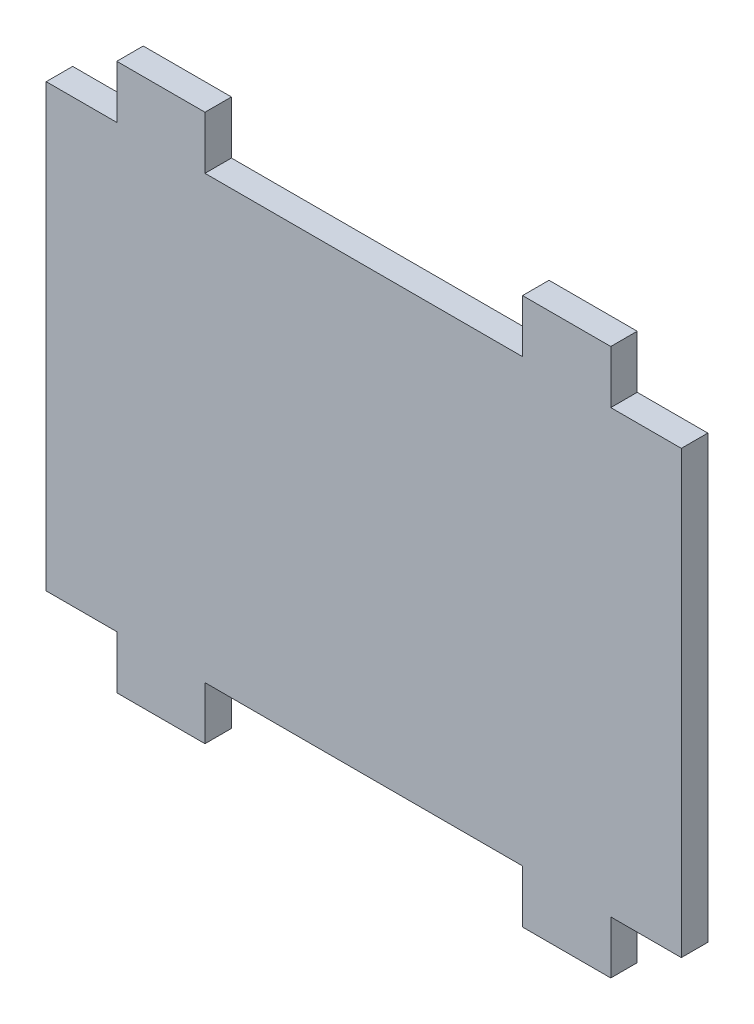
SolidWorks part; units mm, degrees
ref_plane "Plan de face" through (0, 0, 0) normal (0, 0, 1) x (1, 0, 0)
ref_plane "Plan de dessus" through (0, 0, 0) normal (0, 1, 0) x (1, 0, 0)
ref_plane "Plan de droite" through (0, 0, 0) normal (1, 0, 0) x (0, 0, -1)
sketch "Esquisse1" plane through (0, 0, 0) normal (0, 0, 1) x (1, 0, 0)
  line L1 (0, 0) -> (-72, 0)
  line L2 (0, 0) -> (0, 50)
  line L3 (-72, 50) -> (0, 50)
  line L4 (-72, 0) -> (-72, 50)
  dimension "D1" = 50
  dimension "D2" = 72
extrude "Boss.-Extru.1" add sketch "Esquisse1" along normal blind 3
sketch "Esquisse2" plane through (0, 0, 3) normal (0, 0, 1) x (1, 0, 0)
  line L1 (-72, 0) -> (0, 0) construction
  line L2 (-64, 0) -> (-54, 0)
  line L3 (-64, 0) -> (-64, -6)
  line L4 (-64, -6) -> (-54, -6)
  line L5 (-54, 0) -> (-54, -6)
  line L7 (-36, 50) -> (-36, 0) construction
  line L8 (0, 50) -> (-72, 50) construction
  line L10 (-54, 50) -> (-54, 56)
  line L11 (-64, 56) -> (-54, 56)
  line L12 (-64, 50) -> (-64, 56)
  line L13 (-64, 50) -> (-54, 50)
  line L14 (-128, 25) -> (0, 25) construction
  line L15 (-8, 50) -> (-18, 50)
  line L16 (-8, 50) -> (-8, 56)
  line L17 (-8, 56) -> (-18, 56)
  line L18 (-18, 50) -> (-18, 56)
  line L19 (-18, 0) -> (-18, -6)
  line L20 (-8, -6) -> (-18, -6)
  line L21 (-8, 0) -> (-8, -6)
  line L22 (-8, 0) -> (-18, 0)
  dimension "D1" = 18
  dimension "D2" = 6
  dimension "D3" = 0
  dimension "D4" = 10
  dimension "D5" = 25
extrude "Boss.-Extru.2" add sketch "Esquisse2" against normal blind 3
